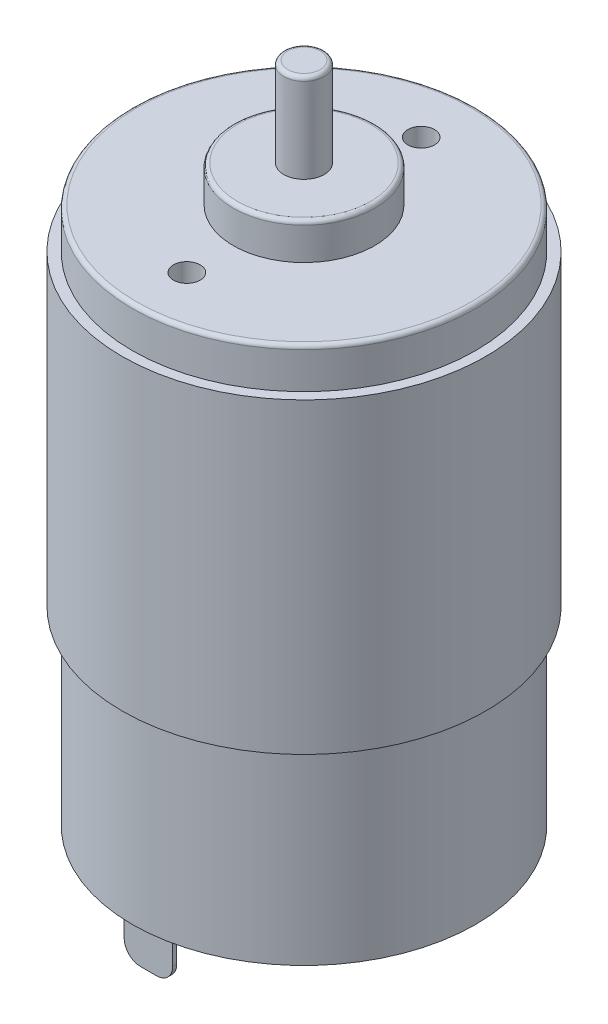
SolidWorks part; units mm, degrees
ref_plane "Спереди" through (0, 0, 0) normal (0, 0, 1) x (1, 0, 0)
ref_plane "Сверху" through (0, 0, 0) normal (0, 1, 0) x (1, 0, 0)
ref_plane "Справа" through (0, 0, 0) normal (1, 0, 0) x (0, 0, -1)
sketch "Эскиз1" plane through (0, 0, 0) normal (0, 0, 1) x (1, 0, 0)
  line L0 (0, 0) -> (0, 93.5)
  line L1 (0, 93.5) -> (2.5, 93.5)
  line L2 (2.5, 93.5) -> (2.5, 82.5)
  line L3 (2.5, 82.5) -> (8.75, 82.5)
  line L4 (8.75, 82.5) -> (8.75, 78)
  line L13 (2.5, 0) -> (0, 0)
  line L14 (8.75, 78) -> (21.25, 78)
  line L15 (21.25, 78) -> (21.25, 73)
  line L16 (21.25, 73) -> (22.5, 73)
  line L17 (22.5, 73) -> (22.5, 35)
  line L18 (22.5, 35) -> (21.25, 35)
  line L19 (21.25, 35) -> (21.25, 11.5)
  line L20 (21.25, 11.5) -> (8.75, 11.5)
  line L21 (8.75, 11.5) -> (8.75, 7.5)
  line L22 (8.75, 7.5) -> (2.5, 7.5)
  line L23 (2.5, 7.5) -> (2.5, 0)
revolve "Повернуть1" add sketch "Эскиз1" angle 360 about L0
sketch "Эскиз2" plane through (0, 11.5, 0) normal (0, -1, 0) x (1, 0, 0)
  line L0 (0, -21.25) -> (0, 21.25) construction
  line L1 (-3, -19.25) -> (3, -19.25)
  line L2 (-3, 18.75) -> (3, 18.75)
  line L3 (-3, 18.75) -> (-3, 19.25)
  line L4 (-3, 19.25) -> (3, 19.25)
  line L5 (3, 18.75) -> (3, 19.25)
  line L6 (-3, -19.25) -> (-3, -18.75)
  line L7 (-3, -18.75) -> (3, -18.75)
  line L8 (3, -19.25) -> (3, -18.75)
  circle A0 centre (0, 0) radius 21.25 construction
  circle A1 centre (0, 0) radius 21.25 construction
  point P11 (0, 19.25)
  point P17 (0, -19.25)
  dimension "D1" = 2
  dimension "D2" = 2
extrude "Бобышка-Вытянуть1" add sketch "Эскиз2" along normal blind 6
sketch "Эскиз3" plane through (0, 78, 0) normal (0, 1, 0) x (1, 0, 0)
  line L0 (0, 0) -> (0, 14.5) construction
  line L1 (0, 0) -> (0, -14.5) construction
  circle A0 centre (0, -14.5) radius 1.65
  circle A1 centre (0, 14.5) radius 1.65
  dimension "D1" = 14.5
  dimension "D2" = 3.3
extrude "Вырез-Вытянуть1" cut sketch "Эскиз3" against normal blind 3.5
fillet "Скругление1" radius 0.5 5 edges at (0, 0, -2.5) (0, 7.5, -8.75) (0, 78, -21.25) (0, 82.5, -8.75) (0, 93.5, -2.5)
fillet "Скругление2" radius 2 4 edges at (3, 5.5, -19) (-3, 5.5, -19) (-3, 5.5, 19) (3, 5.5, 19)
